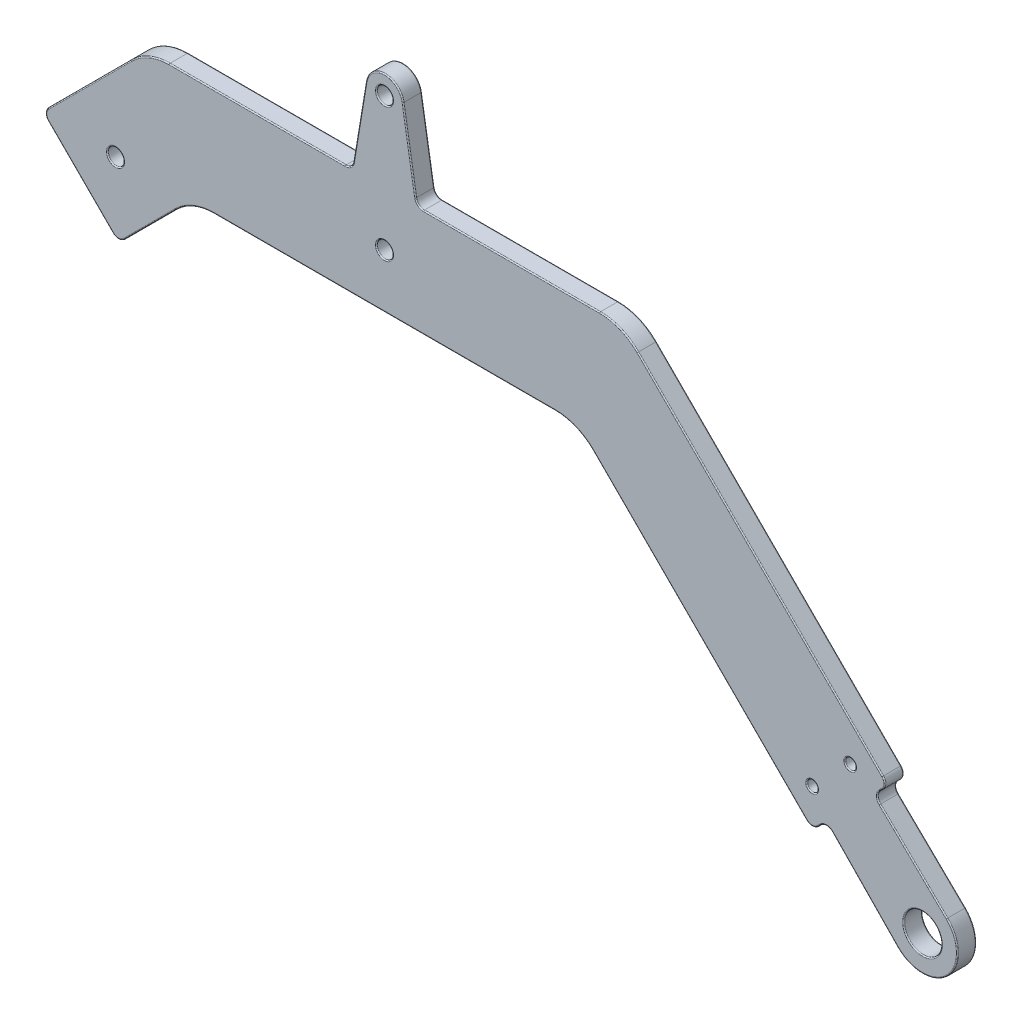
SolidWorks part; units mm, degrees
ref_plane "Front Plane" through (0, 0, 0) normal (0, 0, 1) x (1, 0, 0)
ref_plane "Top Plane" through (0, 0, 0) normal (0, 1, 0) x (1, 0, 0)
ref_plane "Right Plane" through (0, 0, 0) normal (1, 0, 0) x (0, 0, -1)
sketch "Sketch1" plane through (0, 0, 0) normal (0, 0, 1) x (1, 0, 0)
  line L0 (100, 0) -> (-100, 0) construction
  line L1 (-100, 0) -> (0, 100) construction
  line L2 (0, 100) -> (100, 0) construction
  line L3 (0, 0) -> (-50, 50) construction
  line L4 (-40, 60) -> (40, 60) construction
  line L5 (0, 100) -> (0, 60) construction
  circle A0 centre (-100, 0) radius 20
  circle A1 centre (0, 0) radius 20
  circle A2 centre (100, 0) radius 20
  point P2 (0, 0)
  dimension "D5" = 40
  dimension "D1" = 200
  dimension "D2" = 90
  dimension "D3" = 90
  dimension "D4" = 80
sketch "Sketch2" plane through (0, 0, 0) normal (0, 0, 1) x (1, 0, 0)
  line L0 (93.636, 20.5061) -> (79.4939, 6.364)
  line L1 (-56.5165, 43.4835) -> (-40, 60) construction
  line L2 (-100, 0) -> (0, 100) construction
  line L3 (-40, 60) -> (40, 60) construction
  line L4 (40, 60) -> (86.565, 13.435) construction
  line L5 (0, 100) -> (100, 0) construction
  line L6 (-49.4454, 36.4124) -> (-35.8579, 50)
  line L7 (-35.8579, 50) -> (35.8579, 50)
  line L8 (35.8579, 50) -> (79.4939, 6.364)
  line L9 (-63.5876, 50.5546) -> (-44.1421, 70)
  line L10 (-44.1421, 70) -> (44.1421, 70)
  line L11 (44.1421, 70) -> (93.636, 20.5061)
  line L12 (-63.5876, 50.5546) -> (-49.4454, 36.4124)
  line L13 (82.1491, 9.0191) -> (95.3424, -4.534)
  line L14 (90.9809, 17.8509) -> (104.534, 4.6576)
  line L15 (90.1005, 24.0416) -> (75.9584, 9.8995) construction
  line L17 (6, 70) -> (3.4532, 85.4203)
  line L18 (-6, 70) -> (-3.4532, 85.4203)
  line L19 (0, 100) -> (0, 60) construction
  circle A0 centre (100, 0) radius 3.5
  circle A1 centre (100, 0) radius 10 construction
  arc A2 (95.3424, -4.534) -> (104.534, 4.6576) centre (100, 0) ccw
  circle A3 centre (100, 0) radius 20 construction
  circle A4 centre (86.565, 20.5061) radius 1
  circle A5 centre (100, 0) radius 6.5 construction
  circle A6 centre (79.4939, 13.435) radius 1
  circle A7 centre (0, 60) radius 1.5
  circle A8 centre (0, 84.85) radius 1.5
  arc A9 (3.4532, 85.4203) -> (-3.4532, 85.4203) centre (0, 84.85) ccw
  circle A10 centre (-50, 50) radius 1.5
  circle A11 centre (0, 84.85) radius 3.5 construction
  point P32 (106.5, 0)
  point P52 (3.5, 82)
  dimension "D4" = 20
  dimension "D5" = 7
  dimension "D9" = 2
  dimension "D12" = 3
  dimension "D17" = 3
  dimension "D3" = 27.5
  dimension "D7" = 19
  dimension "D8" = 5
  dimension "D10" = 5
  dimension "D11" = 5
  dimension "D13" = 14.85
  dimension "D15" = 6
  dimension "D16" = 6
  dimension "D1" = 10
  dimension "D2" = 10
  dimension "D6" = 3
  dimension "D14" = 2
sketch "Sketch3" plane through (0, 0, 0) normal (0, 0, 1) x (1, 0, 0)
  line L0 (-86.565, 13.435) -> (-50, 50) construction
  line L1 (-100, 0) -> (0, 100) construction
  line L2 (-50, 50) -> (-13.435, 13.435) construction
  line L3 (0, 0) -> (-50, 50) construction
  line L4 (-79.4939, 6.364) -> (-50, 35.8579)
  line L5 (-50, 35.8579) -> (-20.5061, 6.364)
  line L6 (-93.636, 20.5061) -> (-50, 64.1421)
  line L7 (-50, 64.1421) -> (-6.364, 20.5061)
  line L8 (-79.4939, 6.364) -> (-50, 35.8579) construction
  line L9 (-93.636, 20.5061) -> (-50, 64.1421) construction
  line L10 (-93.636, 20.5061) -> (-79.4939, 6.364)
  line L11 (-6.364, 20.5061) -> (-20.5061, 6.364)
  line L12 (-104.534, 4.6576) -> (-90.9809, 17.8509)
  line L13 (-82.1491, 9.0191) -> (-95.3424, -4.534)
  line L14 (-17.8509, 9.0191) -> (-4.6576, -4.534)
  line L15 (-9.0191, 17.8509) -> (4.534, 4.6576)
  line L16 (-9.8995, 24.0416) -> (-24.0416, 9.8995) construction
  line L17 (-90.1005, 24.0416) -> (-75.9584, 9.8995) construction
  circle A0 centre (-100, 0) radius 3.5
  circle A1 centre (-100, 0) radius 10 construction
  circle A2 centre (0, 0) radius 3.5
  circle A3 centre (0, 0) radius 10 construction
  arc A4 (-104.534, 4.6576) -> (-95.3424, -4.534) centre (-100, 0) ccw
  arc A5 (-4.6576, -4.534) -> (4.534, 4.6576) centre (0, 0) ccw
  circle A6 centre (-100, 0) radius 20 construction
  circle A7 centre (0, 0) radius 20 construction
  circle A8 centre (-86.565, 20.5061) radius 1
  circle A9 centre (-100, 0) radius 6.5 construction
  circle A10 centre (0, 0) radius 6.5 construction
  circle A11 centre (-79.4939, 13.435) radius 1
  circle A12 centre (-20.5061, 13.435) radius 1
  circle A13 centre (-13.435, 20.5061) radius 1
  circle A14 centre (-50, 50) radius 1.5 construction
  circle A15 centre (-50, 50) radius 1.5
  point P9 (6.5, 0)
  point P43 (-93.5, 0)
  dimension "D1" = 20
  dimension "D2" = 7
  dimension "D8" = 2
  dimension "D6" = 19
  dimension "D7" = 19
  dimension "D9" = 5
  dimension "D10" = 5
  dimension "D11" = 5
  dimension "D12" = 5
  dimension "D13" = 5
  dimension "D14" = 5
  dimension "D3" = 3
  dimension "D4" = 10
  dimension "D5" = 10
sketch "Sketch4" plane through (0, 0, 0) normal (0, 0, 1) x (1, 0, 0)
  line L0 (-57.5062, 93.35) -> (57.4938, 93.35)
  line L1 (57.4938, 93.35) -> (57.4938, 83.35)
  line L2 (57.4938, 83.35) -> (44.1421, 70)
  line L3 (44.1421, 70) -> (-44.1421, 70)
  line L4 (-44.1421, 70) -> (-57.5062, 83.35)
  line L5 (-57.5062, 83.35) -> (-57.5062, 93.35)
  line L6 (4, 60) -> (4, 70)
  line L7 (-4, 60) -> (-4, 70)
  line L8 (-22.5, 84.85) -> (22.5, 84.85) construction
  line L9 (-22.5, 89.35) -> (22.5, 89.35)
  line L10 (-22.5, 80.35) -> (22.5, 80.35)
  circle A0 centre (0, 60) radius 1.5 construction
  circle A1 centre (0, 60) radius 1.5
  arc A2 (-4, 60) -> (4, 60) centre (0, 60) ccw
  arc A3 (-22.5, 89.35) -> (-22.5, 80.35) centre (-22.5, 84.85) ccw
  circle A4 centre (0, 60) radius 4 construction
  arc A5 (22.5, 80.35) -> (22.5, 89.35) centre (22.5, 84.85) ccw
  point P20 (4, 60)
  point P23 (0, 84.85)
  dimension "D5" = 9
  dimension "D1" = 115
  dimension "D2" = 10
  dimension "D4" = 45
  dimension "D6" = 4
  dimension "D3" = 2.5
sketch "Sketch5" plane through (0, 0, 0) normal (0, 0, 1) x (1, 0, 0)
  line L0 (82.1491, 9.0191) -> (95.3424, -4.534) construction
  line L1 (90.9809, 17.8509) -> (104.534, 4.6576) construction
  line L2 (6, 70) -> (3.4532, 85.4203) construction
  line L3 (-6, 70) -> (-3.4532, 85.4203) construction
  line L4 (82.1491, 9.0191) -> (95.3424, -4.534)
  line L5 (90.9809, 17.8509) -> (104.534, 4.6576)
  line L6 (6, 70) -> (3.4532, 85.4203)
  line L7 (-6, 70) -> (-3.4532, 85.4203)
  line L8 (79.4939, 6.364) -> (93.636, 20.5061)
  line L9 (35.8579, 50) -> (79.4939, 6.364)
  line L10 (-35.8579, 50) -> (35.8579, 50)
  line L11 (-49.4454, 36.4124) -> (-35.8579, 50)
  line L12 (-63.5876, 50.5546) -> (-49.4454, 36.4124)
  line L13 (-44.1421, 70) -> (-63.5876, 50.5546)
  line L14 (44.1421, 70) -> (-44.1421, 70)
  line L15 (93.636, 20.5061) -> (44.1421, 70)
  line L16 (79.4939, 6.364) -> (82.1491, 9.0191)
  line L17 (35.8579, 50) -> (79.4939, 6.364)
  line L18 (-35.8579, 50) -> (35.8579, 50)
  line L19 (-49.4454, 36.4124) -> (-35.8579, 50)
  line L20 (-63.5876, 50.5546) -> (-49.4454, 36.4124)
  line L21 (-44.1421, 70) -> (-63.5876, 50.5546)
  line L22 (44.1421, 70) -> (6, 70)
  line L23 (93.636, 20.5061) -> (44.1421, 70)
  line L24 (-6, 70) -> (-44.1421, 70)
  line L25 (90.9809, 17.8509) -> (93.636, 20.5061)
  arc A0 (95.3424, -4.534) -> (104.534, 4.6576) centre (100, 0) ccw construction
  circle A1 centre (86.565, 20.5061) radius 1
  circle A2 centre (86.565, 20.5061) radius 1
  circle A3 centre (100, 0) radius 3.5
  circle A4 centre (100, 0) radius 3.5
  circle A5 centre (0, 84.85) radius 1.5
  circle A6 centre (0, 84.85) radius 1.5
  circle A7 centre (0, 60) radius 1.5
  circle A8 centre (0, 60) radius 1.5
  circle A9 centre (79.4939, 13.435) radius 1
  circle A10 centre (79.4939, 13.435) radius 1
  circle A11 centre (-50, 50) radius 1.5
  circle A12 centre (-50, 50) radius 1.5
  arc A13 (3.4532, 85.4203) -> (-3.4532, 85.4203) centre (0, 84.85) ccw construction
  arc A14 (95.3424, -4.534) -> (104.534, 4.6576) centre (100, 0) ccw
  arc A15 (3.4532, 85.4203) -> (-3.4532, 85.4203) centre (0, 84.85) ccw
  dimension "D1" = 0
  dimension "D2" = 0
  dimension "D3" = 0
  dimension "D4" = 0
  dimension "D5" = 0
  dimension "D6" = 0
  dimension "D7" = 0
extrude "Boss-Extrude1" add sketch "Sketch5" along normal blind 3.5
fillet "Fillet1" radius 10 4 edges at (-35.8579, 50, 1.75) (35.8579, 50, 1.75) (-44.1421, 70, 1.75) (44.1421, 70, 1.75)
fillet "Fillet2" radius 1.5 8 edges at (-49.4454, 36.4124, 1.75) (-63.5876, 50.5546, 1.75) (-6, 70, 1.75) (6, 70, 1.75) (82.1491, 9.0191, 1.75) (79.4939, 6.364, 1.75) (90.9809, 17.8509, 1.75) (93.636, 20.5061, 1.75)
fillet "Fillet3" radius 0.2 68 edges at (-48.5, 50, 0) (-48.5, 50, 3.5) (80.4939, 13.435, 0) (80.4939, 13.435, 3.5) (1.5, 60, 0) (1.5, 60, 3.5) (1.5, 84.85, 0) (1.5, 84.85, 3.5) (103.5, 0, 0) (103.5, 0, 3.5) (87.565, 20.5061, 0) (87.565, 20.5061, 3.5) (92.3156, 19.1857, 0) (69.8232, 44.3189, 0) (23.6363, 70, 0) (4.6229, 78.3379, 0) (0, 88.35, 0) (-4.6229, 78.3379, 0) (-23.6363, 70, 0) (-54.799, 59.3431, 0) (-56.5165, 43.4835, 0) (-43.5858, 42.2721, 0) (0, 50, 0) (58.61, 27.2478, 0) (80.8143, 7.6844, 0) (89.276, 1.6979, 0) (104.5962, -4.5962, 0) (98.3021, 10.724, 0) (92.3156, 19.1857, 3.5) (69.8232, 44.3189, 3.5) (4.6229, 78.3379, 3.5) (0, 88.35, 3.5) (-4.6229, 78.3379, 3.5) (-23.6363, 70, 3.5) (-54.799, 59.3431, 3.5) (-56.5165, 43.4835, 3.5) (-43.5858, 42.2721, 3.5) (0, 50, 3.5) (58.61, 27.2478, 3.5) (80.8143, 7.6844, 3.5) (89.276, 1.6979, 3.5) (104.5962, -4.5962, 3.5) (98.3021, 10.724, 3.5) (43.8268, 69.2388, 0) (-43.8268, 69.2388, 0) (43.8268, 69.2388, 3.5) (-43.8268, 69.2388, 3.5) (-35.5426, 49.2388, 0) (-35.5426, 49.2388, 3.5) (35.5426, 49.2388, 0) (35.5426, 49.2388, 3.5) (93.0147, 20.5061, 0) (79.4939, 6.9853, 0) (-62.9663, 50.5546, 0) (-49.4454, 37.0337, 0) (93.0147, 20.5061, 3.5) (79.4939, 6.9853, 3.5) (-62.9663, 50.5546, 3.5) (-49.4454, 37.0337, 3.5) (-6.3022, 70.3562, 0) (-6.3022, 70.3562, 3.5) (6.3022, 70.3562, 0) (6.3022, 70.3562, 3.5) (82.1448, 8.3834, 0) (82.1448, 8.3834, 3.5) (91.6166, 17.8552, 0) (91.6166, 17.8552, 3.5) (23.6363, 70, 3.5)
